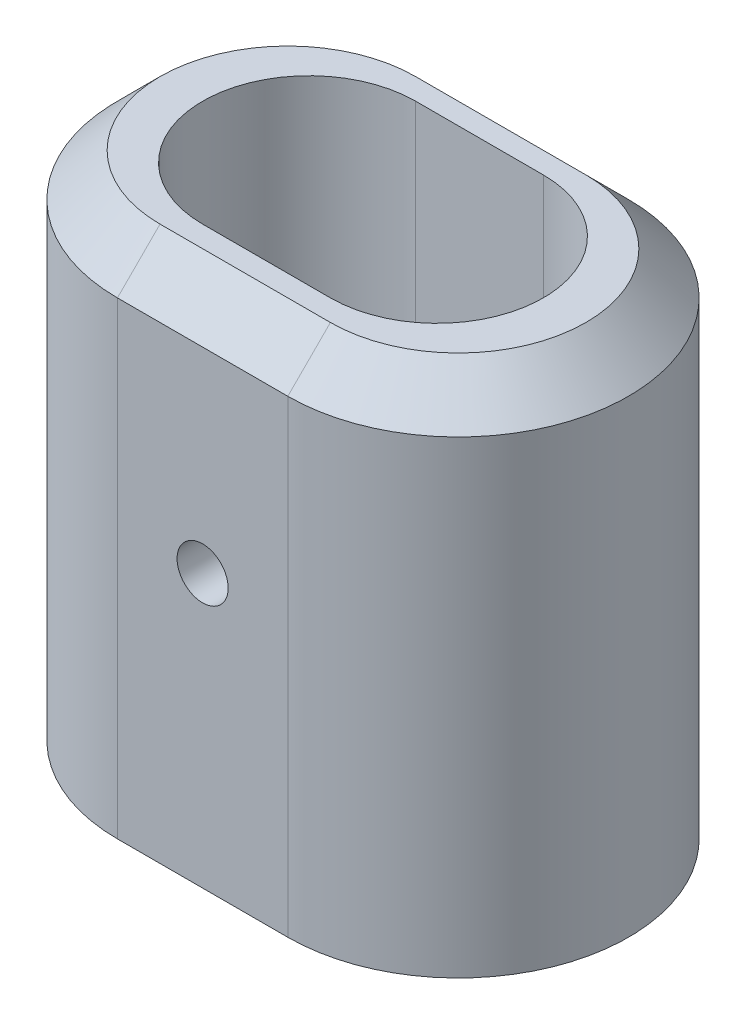
SolidWorks part; units mm, degrees
material "AISI 1020"
ref_plane "Alzado" through (0, 0, 0) normal (0, 0, 1) x (1, 0, 0)
ref_plane "Planta" through (0, 0, 0) normal (0, 1, 0) x (1, 0, 0)
ref_plane "Vista lateral" through (0, 0, 0) normal (1, 0, 0) x (0, 0, -1)
sketch "Croquis2" plane through (0, 0, 0) normal (0, 1, 0) x (1, 0, 0)
  line L0 (-20, 0) -> (20, 0) construction
  line L1 (-7.5, 0) -> (-20, 0) construction
  line L2 (7.5, 0) -> (20, 0) construction
  line L3 (-7.5, 12.5) -> (7.5, 12.5)
  line L4 (-7.5, -12.5) -> (7.5, -12.5)
  line L5 (-30, 0) -> (30, 0) construction
  line L6 (-10, 20) -> (10, 20)
  line L7 (-10, -20) -> (10, -20)
  arc A0 (-7.5, 12.5) -> (-7.5, -12.5) centre (-7.5, 0) ccw
  arc A1 (7.5, -12.5) -> (7.5, 12.5) centre (7.5, 0) ccw
  arc A4 (-10, 20) -> (-10, -20) centre (-10, 0) ccw
  arc A5 (10, -20) -> (10, 20) centre (10, 0) ccw
  point P3 (0, 0)
  point P4 (0, 0)
  dimension "D2" = 25
  dimension "D3" = 25
  dimension "D4" = 60
  dimension "D5" = 40
  dimension "D6" = 40
  dimension "D7" = 20
  dimension "D1" = 40
  dimension "D8" = 20
extrude "Saliente-Extruir1" add sketch "Croquis2" along normal blind 60
chamfer "Chaflán2" distance 5 angle 45 4 edges at (-30, 60, 0) (0, 60, 20) (0, 60, -20) (30, 60, 0)
ref_plane "Plano3" through (0, 0, 20) normal (0, 0, 1) x (1, 0, 0)
sketch "Croquis6" plane through (0, 0, 20) normal (0, 0, 1) x (1, 0, 0)
  line L0 (-10, 60) -> (10, 60) construction
  line L1 (-30, 55) -> (-30, 0) construction
  circle A0 centre (0, 32) radius 3
  dimension "D1" = 6
  dimension "D2" = 28
  dimension "D3" = 30
extrude "Cortar-Extruir1" cut sketch "Croquis6" against normal blind 40
